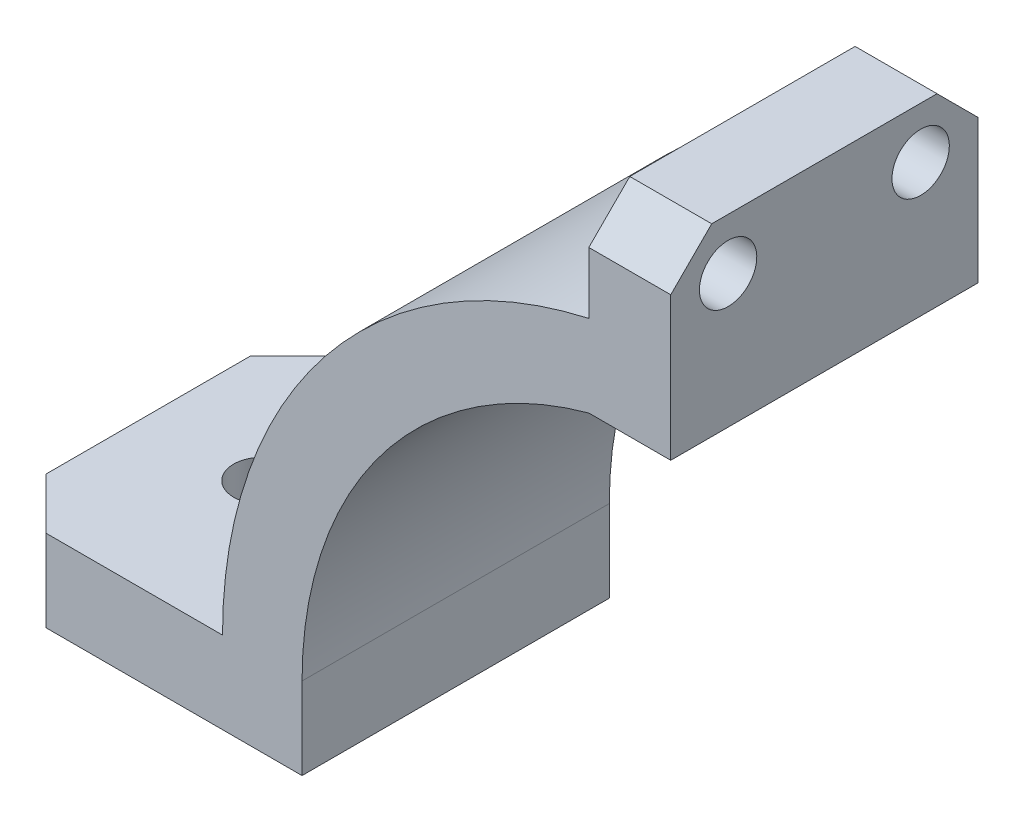
SolidWorks part; units mm, degrees
ref_plane "Front Plane" through (0, 0, 0) normal (0, 0, 1) x (1, 0, 0)
ref_plane "Top Plane" through (0, 0, 0) normal (0, 1, 0) x (1, 0, 0)
ref_plane "Right Plane" through (0, 0, 0) normal (1, 0, 0) x (0, 0, -1)
sketch "Sketch1" plane through (0, 0, 0) normal (0, 0, 1) x (1, 0, 0)
  line L0 (0, 0) -> (0, 50000) construction
  line L2 (-19, 0) -> (-19, -4)
  line L3 (-19, -4) -> (-34, -4)
  line L4 (-34, -4) -> (-34, 0)
  line L5 (-34, 0) -> (-22.8832, 0)
  line L6 (-5, 22.3303) -> (-5, 27.3303)
  line L7 (-5, 27.3303) -> (-1, 27.3303)
  line L8 (-1, 27.3303) -> (-1, 18.3303)
  line L9 (-1, 18.3303) -> (-5, 18.3303)
  arc A0 (-19, 0) -> (-5, 18.3303) centre (0, 0) cw
  arc A1 (-22.8832, 0) -> (-5, 22.3303) centre (0, 0) cw
  dimension "D2" = 19
  dimension "D1" = 4
  dimension "D3" = 15
  dimension "D4" = 4
  dimension "D5" = 4
  dimension "D6" = 9
  dimension "D7" = 1
extrude "Boss-Extrude1" add sketch "Sketch1" along normal blind 15
chamfer "Chamfer1" distance 2.5 2 edges at (-34, -2, 0) (-34, -2, 15)
sketch "Sketch2" plane through (-5, 0, 0) normal (-1, 0, 0) x (0, 0, 1)
  line L0 (15, 27.3303) -> (15, 22.3303) construction
  line L1 (0, 27.3303) -> (0, 22.3303) construction
  circle A0 centre (2.8, 24.8303) radius 1.4
  circle A1 centre (12.2, 24.8303) radius 1.4
  point P8 (0, 24.8303)
  dimension "D1" = 2.8
  dimension "D2" = 2.8
  dimension "D3" = 2.8
extrude "Cut-Extrude1" cut sketch "Sketch2" against normal blind 15
chamfer "Chamfer2" distance 2 angle 45 2 edges at (-3, 27.3303, 15) (-3, 27.3303, 0)
sketch "Sketch3" plane through (0, 0, 0) normal (0, 1, 0) x (1, 0, 0)
  line L0 (-34, -12.5) -> (-34, -2.5) construction
  line L2 (-22.8832, 0) -> (-34, 0.1) construction
  line L3 (45.4373, 0.1) -> (-44.4791, 0.1) construction
  circle A0 centre (-28.4416, -7.5) radius 1.4
  point P2 (-28.4416, 0.05)
  point P5 (-34, -7.5)
  dimension "D1" = 2.8
extrude "Cut-Extrude2" cut sketch "Sketch3" against normal through all contours A0
